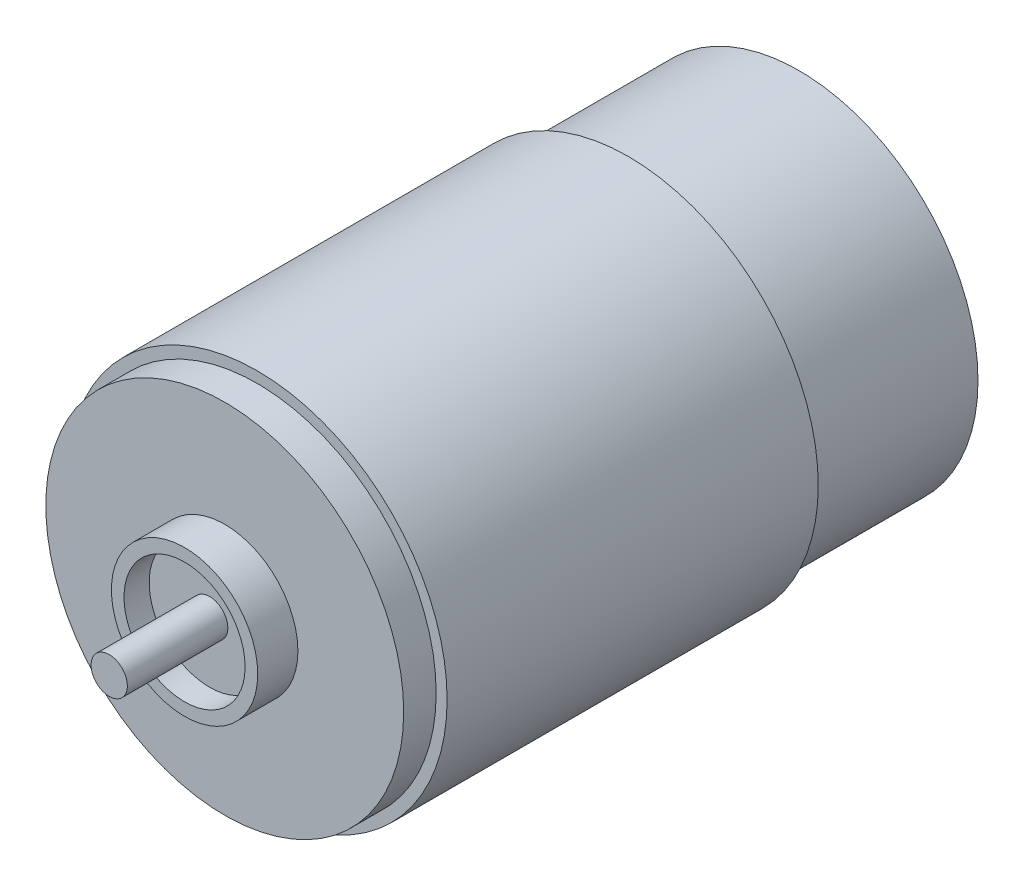
SolidWorks part; units mm, degrees
ref_plane "前视基准面" through (0, 0, 0) normal (0, 0, 1) x (1, 0, 0)
ref_plane "上视基准面" through (0, 0, 0) normal (0, 1, 0) x (1, 0, 0)
ref_plane "右视基准面" through (0, 0, 0) normal (1, 0, 0) x (0, 0, -1)
sketch "草图1" plane through (0, 0, 0) normal (0, 0, 1) x (1, 0, 0)
  circle A0 centre (0, 0) radius 18.9
extrude "凸台-拉伸1" add sketch "草图1" along normal blind 36.94
sketch "草图2" plane through (0, 0, 36.94) normal (0, 0, 1) x (1, 0, 0)
  circle A0 centre (0, 0) radius 17.81
extrude "凸台-拉伸2" add sketch "草图2" along normal blind 3.23
sketch "草图3" plane through (0, 0, 0) normal (0, 0, -1) x (-1, 0, 0)
  circle A0 centre (0, 0) radius 17.81
extrude "凸台-拉伸3" add sketch "草图3" along normal blind 16.99
sketch "草图4" plane through (0, 0, -16.99) normal (0, 0, -1) x (-1, 0, 0)
  circle A0 centre (0, 0) radius 16.485
extrude "切除-拉伸1" cut sketch "草图4" against normal blind 1.38
sketch "草图5" plane through (0, 0, -15.61) normal (0, 0, -1) x (-1, 0, 0)
  circle A0 centre (0, 0) radius 12.15
extrude "凸台-拉伸4" add sketch "草图5" along normal blind 1
sketch "草图6" plane through (0, 0, -16.61) normal (0, 0, -1) x (-1, 0, 0)
  circle A0 centre (0, 0) radius 5.125
extrude "凸台-拉伸5" add sketch "草图6" along normal blind 4
sketch "草图7" plane through (0, 0, -20.61) normal (0, 0, -1) x (-1, 0, 0)
  circle A0 centre (0, 0) radius 4.4999
extrude "切除-拉伸2" cut sketch "草图7" against normal blind 1
sketch "草图8" plane through (0, 0, -19.61) normal (0, 0, -1) x (-1, 0, 0)
  circle A0 centre (0, 0) radius 1.2752
extrude "凸台-拉伸6" add sketch "草图8" along normal blind 4
sketch "草图9" plane through (0, 0, 40.17) normal (0, 0, 1) x (1, 0, 0)
  circle A0 centre (0, 0) radius 7.2805
extrude "凸台-拉伸7" add sketch "草图9" along normal blind 4
sketch "草图10" plane through (0, 0, 44.17) normal (0, 0, 1) x (1, 0, 0)
  circle A0 centre (0, 0) radius 6.0241
extrude "切除-拉伸3" cut sketch "草图10" against normal blind 2.5
sketch "草图11" plane through (0, 0, 41.67) normal (0, 0, 1) x (1, 0, 0)
  circle A0 centre (0, 0) radius 1.8053
extrude "凸台-拉伸9" add sketch "草图11" along normal blind 10
